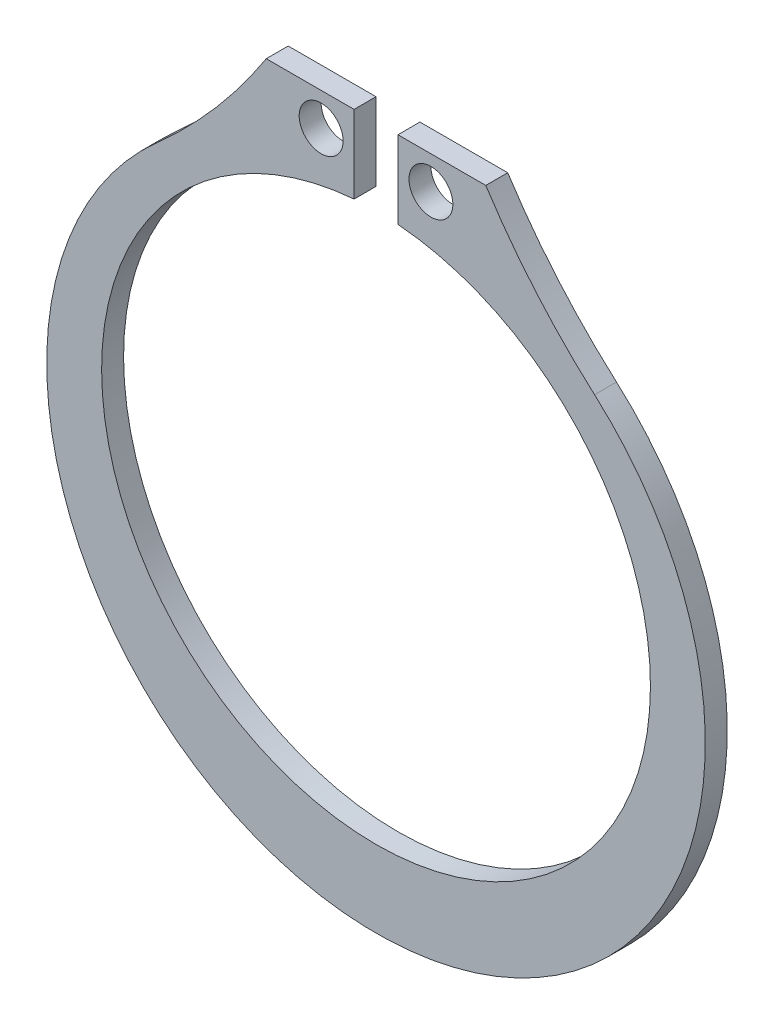
SolidWorks part; units mm, degrees
material "Alloy Steel"
ref_plane "Front Plane" through (0, 0, 0) normal (0, 0, 1) x (1, 0, 0)
ref_plane "Top Plane" through (0, 0, 0) normal (0, 1, 0) x (1, 0, 0)
ref_plane "Right Plane" through (0, 0, 0) normal (1, 0, 0) x (0, 0, -1)
sketch "Sketch1" plane through (0, 0, 0) normal (0, 0, 1) x (1, 0, 0)
  line L0 (0, 0) -> (0, 9.7102) construction
  line L1 (-5, 17) -> (-1, 17)
  line L2 (-1, 17) -> (-1, 13.4599)
  line L3 (1, 17) -> (1, 13.4599)
  line L4 (5, 17) -> (1, 17)
  arc A0 (-9.9549, 11.2205) -> (9.9549, 11.2205) centre (0, 0) ccw
  arc A2 (-1, 13.4599) -> (1, 13.4599) centre (0, 1) ccw
  arc A3 (-5, 17) -> (-9.9549, 11.2205) centre (-28.5374, 32.1655) cw
  arc A4 (5, 17) -> (9.9549, 11.2205) centre (28.5374, 32.1655) ccw
  circle A5 centre (-2.5, 15.5) radius 1
  circle A6 centre (2.5, 15.5) radius 1
  point P16 (0, 0)
  point P19 (-3.1935, 13.3479)
  dimension "D1" = 30
  dimension "D2" = 1
  dimension "D3" = 25
  dimension "D4" = 28
  dimension "D8" = 2
  dimension "D5" = 16
  dimension "D6" = 10
  dimension "D7" = 2
  dimension "D9" = 1.5
  dimension "D10" = 1.5
extrude "Boss-Extrude1" add sketch "Sketch1" along normal blind 1
